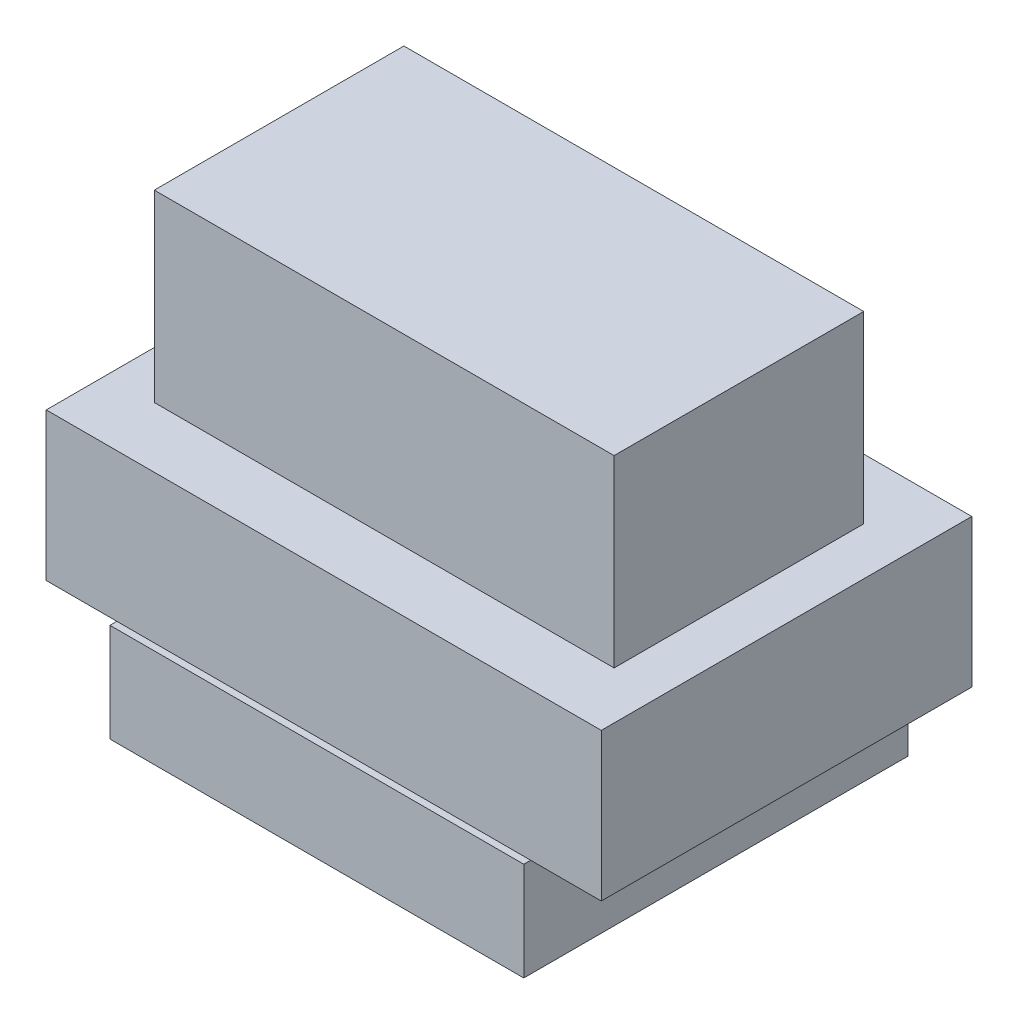
SolidWorks part; units mm, degrees
ref_plane "Front Plane" through (0, 0, 0) normal (0, 0, 1) x (1, 0, 0)
ref_plane "Top Plane" through (0, 0, 0) normal (0, 1, 0) x (1, 0, 0)
ref_plane "Right Plane" through (0, 0, 0) normal (1, 0, 0) x (0, 0, -1)
sketch "Sketch1" plane through (0, 0, 0) normal (0, 1, 0) x (1, 0, 0)
  line L1 (-31.5, -29.25) -> (31.5, -29.25)
  line L2 (-31.5, -29.25) -> (-31.5, 29.25)
  line L3 (-31.5, 29.25) -> (31.5, 29.25)
  line L4 (31.5, -29.25) -> (31.5, 29.25)
  line L5 (-31.5, -29.25) -> (31.5, 29.25) construction
  line L6 (-31.5, 29.25) -> (31.5, -29.25) construction
  point P0 (0, 0)
  dimension "D1" = 58.5
  dimension "D2" = 63
extrude "Boss-Extrude1" add sketch "Sketch1" along normal blind 15
sketch "Sketch2" plane through (0, 15, 0) normal (0, 1, 0) x (1, 0, 0)
  line L1 (-42.25, -28.2) -> (42.25, -28.2)
  line L2 (-42.25, -28.2) -> (-42.25, 28.2)
  line L3 (-42.25, 28.2) -> (42.25, 28.2)
  line L4 (42.25, -28.2) -> (42.25, 28.2)
  line L5 (-42.25, -28.2) -> (42.25, 28.2) construction
  line L6 (-42.25, 28.2) -> (42.25, -28.2) construction
  point P0 (0, 0)
  dimension "D1" = 56.4
  dimension "D2" = 84.5
extrude "Boss-Extrude2" add sketch "Sketch2" along normal blind 22.5
sketch "Sketch3" plane through (0, 37.5, 0) normal (0, 1, 0) x (1, 0, 0)
  line L1 (-35, -19) -> (35, -19)
  line L2 (-35, -19) -> (-35, 19)
  line L3 (-35, 19) -> (35, 19)
  line L4 (35, -19) -> (35, 19)
  line L5 (-35, -19) -> (35, 19) construction
  line L6 (-35, 19) -> (35, -19) construction
  point P0 (0, 0)
  dimension "D1" = 38
  dimension "D2" = 70
extrude "Boss-Extrude3" add sketch "Sketch3" along normal blind 28
